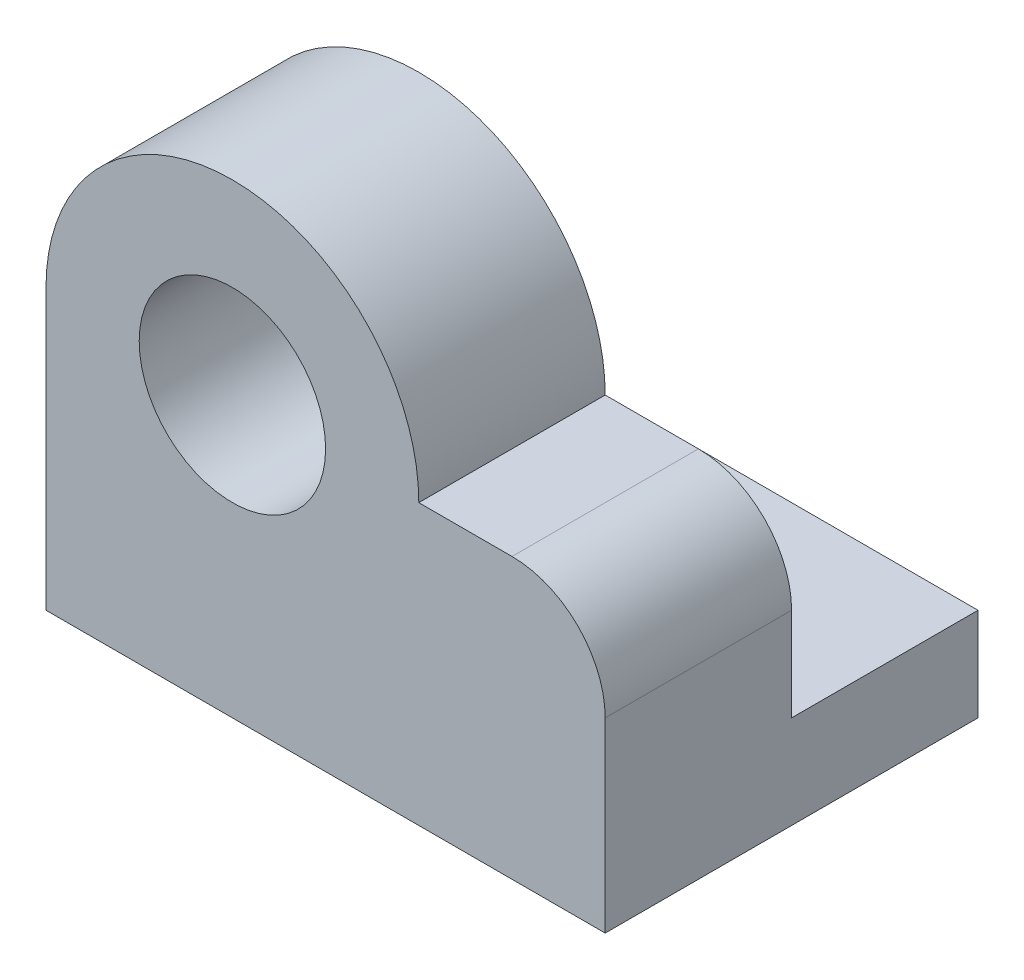
SolidWorks part; units mm, degrees
ref_plane "Front Plane" through (0, 0, 0) normal (0, 0, 1) x (1, 0, 0)
ref_plane "Top Plane" through (0, 0, 0) normal (0, 1, 0) x (1, 0, 0)
ref_plane "Right Plane" through (0, 0, 0) normal (1, 0, 0) x (0, 0, -1)
sketch "Sketch1" plane through (0, 0, 0) normal (0, 0, 1) x (1, 0, 0)
  line L0 (20, 0) -> (30, 0)
  line L2 (40, -10) -> (40, -20)
  line L3 (40, -20) -> (-20, -20)
  line L4 (-20, 0) -> (-20, -20)
  arc A1 (20, 0) -> (-20, 0) centre (0, 0) ccw
  arc A2 (40, -10) -> (30, 0) centre (30, -10) ccw
  dimension "D1" = 60
  dimension "D2" = 40
  dimension "D3" = 10
  dimension "D4" = 20
  dimension "D5" = 10
extrude "Boss-Extrude4" add sketch "Sketch1" along normal blind 20 contours A1 L4 L3 L2 A2 L0
sketch "Sketch6" plane through (0, 0, 20) normal (0, 0, 1) x (1, 0, 0)
  line L0 (40, -20) -> (40, -30)
  line L1 (40, -30) -> (-20, -30)
  line L2 (-20, -30) -> (-20, -20)
  line L3 (-20, -20) -> (40, -20)
  dimension "D1" = 10
extrude "Boss-Extrude6" add sketch "Sketch6" against normal blind 40
sketch "Sketch7" plane through (0, 0, 0) normal (0, 0, -1) x (-1, 0, 0)
  circle A0 centre (0, 0) radius 10
  dimension "D1" = 20
extrude "Cut-Extrude2" cut sketch "Sketch7" against normal blind 40
